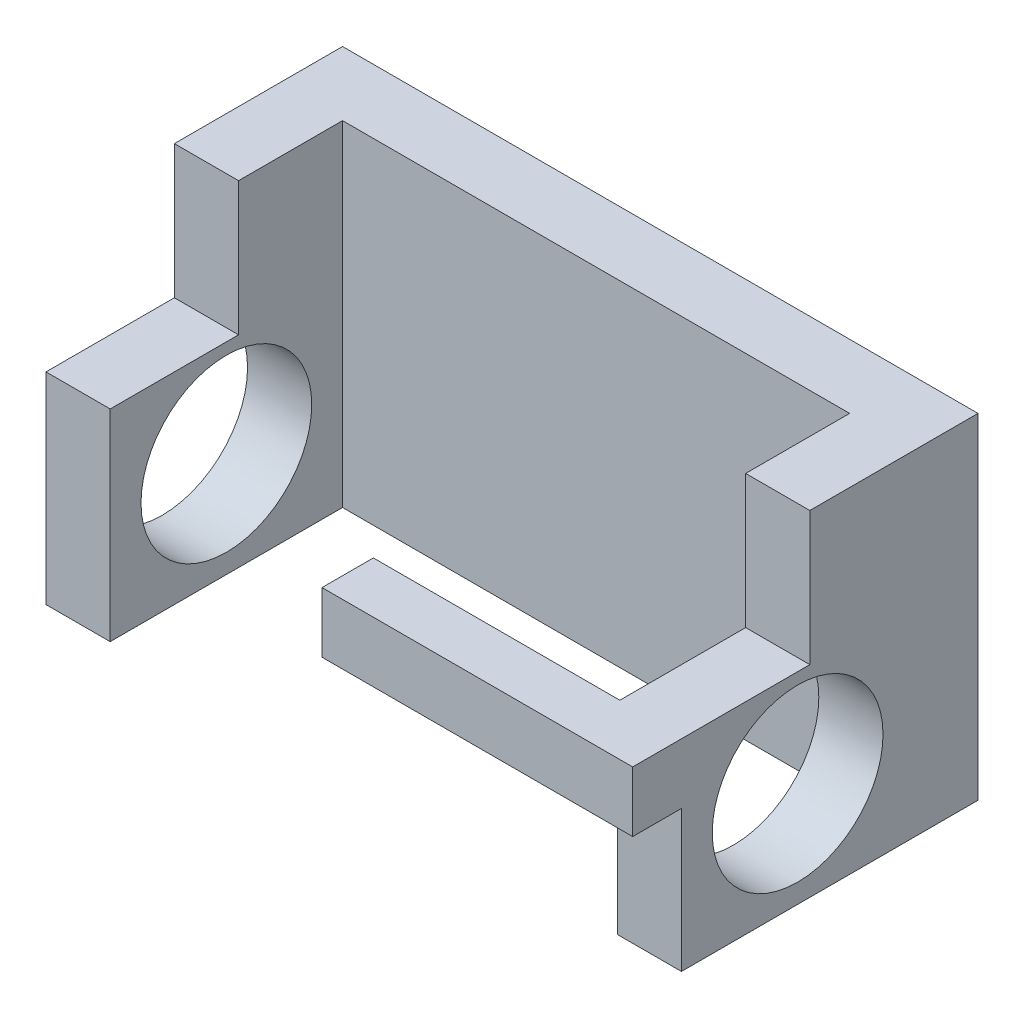
SolidWorks part; units mm, degrees
ref_plane "Alzado" through (0, 0, 0) normal (0, 0, 1) x (1, 0, 0)
ref_plane "Planta" through (0, 0, 0) normal (0, 1, 0) x (1, 0, 0)
ref_plane "Vista lateral" through (0, 0, 0) normal (1, 0, 0) x (0, 0, -1)
sketch "Croquis2" plane through (0, 0, 0) normal (0, 1, 0) x (1, 0, 0)
  line L1 (0, 0) -> (-49.5, 0)
  line L2 (0, 0) -> (0, -26.9)
  line L3 (0, -26.9) -> (-49.5, -26.9)
  line L4 (-49.5, 0) -> (-49.5, -26.9)
  dimension "D1" = 49.5
  dimension "D2" = 26.9
extrude "Saliente-Extruir1" add sketch "Croquis2" along normal blind 26.1
sketch "Croquis3" plane through (0, 0, 0) normal (1, 0, 0) x (0, 0, -1)
  line L0 (-26.9, 15.7) -> (-13.1, 15.7)
  line L1 (-26.9, 26.1) -> (-26.9, 0) construction
  line L2 (-13.1, 15.7) -> (-13.1, 26.1)
  line L3 (-26.9, 26.1) -> (0, 26.1) construction
  line L8 (-13.1, 26.1) -> (-26.9, 26.1)
  line L9 (-26.9, 26.1) -> (-26.9, 15.7)
  dimension "D1" = 13.8
  dimension "D2" = 10.4
sketch "Croquis6" plane through (0, 26.1, 0) normal (0, 1, 0) x (1, 0, 0)
  line L4 (-44.5, -21.9) -> (-44.5, -22.9)
  line L5 (-44.5, -22.9) -> (-25.3, -22.9)
  line L6 (-25.3, -22.9) -> (-25.3, -26.9)
  line L7 (-49.5, -26.9) -> (0, -26.9) construction
  line L8 (-5, -21.9) -> (-5, -5)
  line L9 (-5, -5) -> (-44.5, -5)
  line L10 (-44.5, -5) -> (-44.5, -21.9)
  line L11 (-44.5, -21.9) -> (-5, -21.9)
  line L12 (-5, -21.9) -> (-5, -5)
  line L13 (-5, -5) -> (-44.5, -5)
  line L14 (-44.5, -5) -> (-44.5, -21.9)
  line L16 (-25.3, -26.9) -> (-5, -26.9)
  line L17 (-5, -26.9) -> (-5, -21.9)
  dimension "D2" = 1
  dimension "D3" = 19.2
  dimension "D1" = 5
extrude "Cortar-Extruir2" cut sketch "Croquis6" against normal up to surface (26.1 mm away) up to face at (-24.75, 0, 13.45)
extrude "Cortar-Extruir3" cut sketch "Croquis3" against normal up to next
sketch "Croquis8" plane through (0, 0, 0) normal (1, 0, 0) x (0, 0, -1)
  line L0 (-26.9, 8.15) -> (-14.05, 8.15) construction
  line L1 (-26.9, 15.7) -> (-26.9, 0) construction
  line L2 (-14.05, 8.15) -> (-14.05, 0) construction
  line L3 (-26.9, 0) -> (0, 0) construction
  circle A0 centre (-14.05, 8.15) radius 6.65
  dimension "D1" = 12.85
  dimension "D2" = 8.15
sketch "Croquis9" plane through (-44.5, 0, 0) normal (1, 0, 0) x (0, 0, -1)
  circle A0 centre (-14.05, 8.15) radius 6.65 construction
  circle A1 centre (-14.05, 8.15) radius 6.65
extrude "Cortar-Extruir4" cut sketch "Croquis9" against normal up to next
extrude "Cortar-Extruir5" cut sketch "Croquis8" against normal up to next
sketch "Croquis10" plane through (0, 0, 26.9) normal (0, 0, 1) x (1, 0, 0)
  line L0 (-25.3, 0) -> (-25.3, 26.1) construction
  line L1 (-49.5, 0) -> (-25.3, 0)
  line L2 (-49.5, 0) -> (-49.5, 11)
  line L3 (-49.5, 11) -> (-25.3, 11)
  line L4 (-25.3, 0) -> (-25.3, 11)
  dimension "D1" = 11
sketch "Croquis11" plane through (0, 26.1, 0) normal (0, 1, 0) x (1, 0, 0)
  line L0 (-47.0606, 0) -> (-47.0606, -13.1) construction
  line L1 (0, 0) -> (-49.5, 0) construction
  line L2 (-44.5, -13.1) -> (-49.5, -13.1)
  line L3 (-44.5, -5) -> (-44.5, -22.9) construction
  line L4 (-49.5, 0) -> (-49.5, -26.9) construction
  line L5 (-49.5, -13.1) -> (-49.5, -26.9)
  line L6 (-49.5, -26.9) -> (-25.3, -26.9)
  line L7 (-25.3, -26.9) -> (-25.3, -22.9)
  line L8 (-44.5, -22.9) -> (-25.3, -22.9) construction
  line L9 (-25.3, -22.9) -> (-25.3, -26.9) construction
  line L10 (-25.3, -22.9) -> (-44.5, -22.9)
  line L11 (-44.5, -22.9) -> (-44.5, -13.1)
  dimension "D1" = 13.1
extrude "Cortar-Extruir6" cut sketch "Croquis11" against normal blind 10.4
extrude "Cortar-Extruir7" cut sketch "Croquis10" against normal blind 3.8
sketch "Croquis13" plane through (0, 0, 22.9) normal (0, 0, -1) x (-1, 0, 0)
  line L0 (25.3, 11) -> (49.5, 11) construction
  line L1 (25.3, 11) -> (44.5, 11)
  line L3 (44.5, 0) -> (44.5, 15.7) construction
  line L4 (25.3, 0) -> (44.5, 0)
  line L5 (25.3, 0) -> (25.3, 11)
  line L6 (25.3, 11) -> (44.5, 11)
  line L7 (44.5, 0) -> (44.5, 11)
  line M2 (25.3, 15.7) -> (25.3, 0)
  line M3 (25.3, 0) -> (44.5, 0)
  line M4 (44.5, 0) -> (44.5, 15.7)
extrude "Cortar-Extruir8" cut sketch "Croquis13" against normal up to surface (0.2 mm away) contours L1 M2 M3 M4 up to face at (-37.4, 5.5, 23.1)
sketch "Croquis14" plane through (0, 0, 0) normal (1, 0, 0) x (0, 0, -1)
  line L1 (-26.9, 0) -> (0, 0) construction
  line L2 (-26.9, 15.7) -> (-23.1, 15.7)
  line L3 (-26.9, 15.7) -> (-26.9, 0)
  line L4 (-26.9, 0) -> (-23.1, 0)
  line L5 (-23.1, 15.7) -> (-23.1, 0)
  line L6 (-13.1, 15.7) -> (-13.1, 26.1) construction
  dimension "D1" = 10
extrude "Cortar-Extruir9" cut sketch "Croquis14" against normal up to next
sketch "Croquis16" plane through (-5, 0, 0) normal (-1, 0, 0) x (0, 0, 1)
  line L4 (22.9, 11) -> (26.9, 11)
  line L5 (22.9, 15.7) -> (22.9, 11)
  line L6 (26.9, 15.7) -> (22.9, 15.7)
  line L7 (26.9, 11) -> (26.9, 15.7)
  line L8 (22.9, 11) -> (26.9, 11)
  line L9 (22.9, 15.7) -> (22.9, 11)
  line L10 (26.9, 15.7) -> (22.9, 15.7)
  line L11 (26.9, 11) -> (26.9, 15.7)
  dimension "D1" = 0
extrude "Saliente-Extruir2" add sketch "Croquis16" along normal blind 19.2
sketch "Croquis17" plane through (-5, 0, 0) normal (1, 0, 0) x (0, 0, -1)
  line L4 (-26.9, 11) -> (-23.1, 11)
  line L5 (-23.1, 11) -> (-23.1, 15.7)
  line L6 (-23.1, 15.7) -> (-26.9, 15.7)
  line L7 (-26.9, 15.7) -> (-26.9, 11)
  line L8 (-26.9, 11) -> (-23.1, 11)
  line L9 (-23.1, 11) -> (-23.1, 15.7)
  line L10 (-23.1, 15.7) -> (-26.9, 15.7)
  line L11 (-26.9, 15.7) -> (-26.9, 11)
  dimension "D1" = 0
extrude "Saliente-Extruir3" add sketch "Croquis17" along normal up to surface (5 mm away) up to face at (0, 8.15, 7.4)
sketch "Croquis18" plane through (0, 11, 0) normal (0, -1, 0) x (1, 0, 0)
  line L6 (-25.3, 26.9) -> (-49.5, 26.9)
  line L7 (-49.5, 26.9) -> (-49.5, 23.1)
  line L8 (-49.5, 23.1) -> (-44.5, 23.1)
  line L9 (-44.5, 23.1) -> (-44.5, 22.9)
  line L10 (-44.5, 22.9) -> (-25.3, 22.9)
  line L11 (-25.3, 22.9) -> (-25.3, 26.9)
  line L12 (-25.3, 26.9) -> (-49.5, 26.9)
  line L13 (-49.5, 26.9) -> (-49.5, 23.1)
  line L14 (-49.5, 23.1) -> (-44.5, 23.1)
  line L15 (-44.5, 23.1) -> (-44.5, 22.9)
  line L16 (-44.5, 22.9) -> (-25.3, 22.9)
  line L17 (-25.3, 22.9) -> (-25.3, 26.9)
  dimension "D1" = 0
extrude "Cortar-Extruir10" cut sketch "Croquis18" against normal up to next
